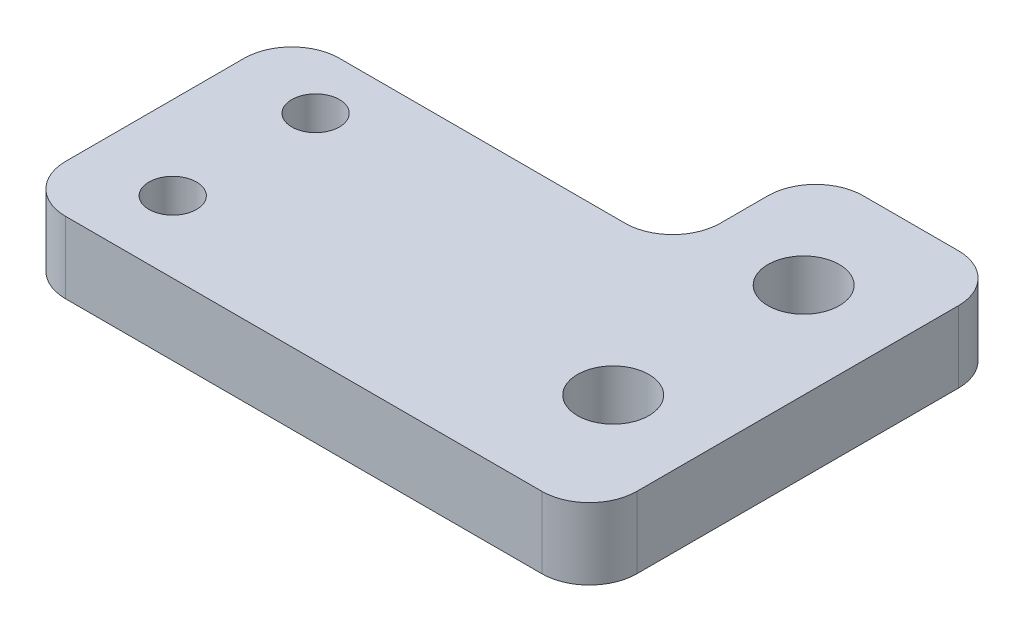
SolidWorks part; units mm, degrees
material "Thornel Mat VMA"
ref_plane "前视基准面" through (0, 0, 0) normal (0, 0, 1) x (1, 0, 0)
ref_plane "上视基准面" through (0, 0, 0) normal (0, 1, 0) x (1, 0, 0)
ref_plane "右视基准面" through (0, 0, 0) normal (1, 0, 0) x (0, 0, -1)
other "Configuration Table"
sketch "草图1" plane through (0, 0, 0) normal (0, 1, 0) x (1, 0, 0)
  line L0 (0, 0) -> (0, 16.3617) construction
  line L1 (-17.5, -9) -> (17.5, -9)
  line L2 (-17.5, -9) -> (-17.5, 9)
  line L3 (-17.5, 9) -> (17.5, 9)
  line L4 (17.5, -9) -> (17.5, 9)
  line L5 (-17.5, -9) -> (17.5, 9) construction
  line L6 (-17.5, 9) -> (17.5, -9) construction
  line L7 (0, 0) -> (24.482, 0) construction
  line L8 (-17.5, 2.5) -> (-1.5, 2.5)
  line L9 (-1.5, 2.5) -> (-1.5, 9)
  circle A0 centre (2.5, 4) radius 1.5
  circle A1 centre (2.5, -4) radius 1.5
  circle A2 centre (-14, 0) radius 1
  circle A3 centre (-14, -6) radius 1
  point P0 (0, 0)
  dimension "D1" = 3
  dimension "D2" = 3
  dimension "D5" = 8
  dimension "D6" = 15
  dimension "D7" = 15
  dimension "D8" = 4
  dimension "D9" = 2
  dimension "D11" = 9
  dimension "D14" = 2
  dimension "D15" = 14
  dimension "D3" = 35
  dimension "D4" = 18
  dimension "D10" = 14
  dimension "D12" = 16
  dimension "D13" = 6.5
  dimension "D16" = 3
extrude "凸台-拉伸1" add sketch "草图1" along normal blind 3
sketch "草图2" plane through (0, 3, 0) normal (0, 1, 0) x (1, 0, 0)
  line L0 (17.5, 9) -> (6.5, 9)
  line L2 (6.5, 9) -> (6.5, -9)
  line L3 (-17.5, -9) -> (17.5, -9) construction
  line L4 (6.5, -9) -> (17.5, -9)
  line L5 (17.5, -9) -> (17.5, 9)
  line L6 (6.5, 9) -> (-1.5, 9)
  line L7 (-1.5, 9) -> (17.5, 9) construction
  line L8 (-1.5, 9) -> (-1.5, 8.5)
  line L9 (-1.5, 2.5) -> (-1.5, 9) construction
  line L10 (-1.5, 8.5) -> (6.5, 8.5)
  line M9 (-1.5, 9) -> (-1.5, 2.5)
  line M12 (-17.5, -9) -> (17.5, -9)
  line M13 (17.5, -9) -> (17.5, 9)
  line M14 (17.5, 9) -> (-1.5, 9)
  dimension "D1" = 11
  dimension "D2" = 0.5
extrude "切除-拉伸1" cut sketch "草图2" against normal blind 10 contours L10 L2 M9 M14 | L2 M14 M12 M13
fillet "圆角1" radius 2 6 edges at (-17.5, 1.5, 9) (-17.5, 1.5, -2.5) (-1.5, 1.5, -2.5) (6.5, 1.5, 9) (6.5, 1.5, -8.5) (-1.5, 1.5, -8.5)
